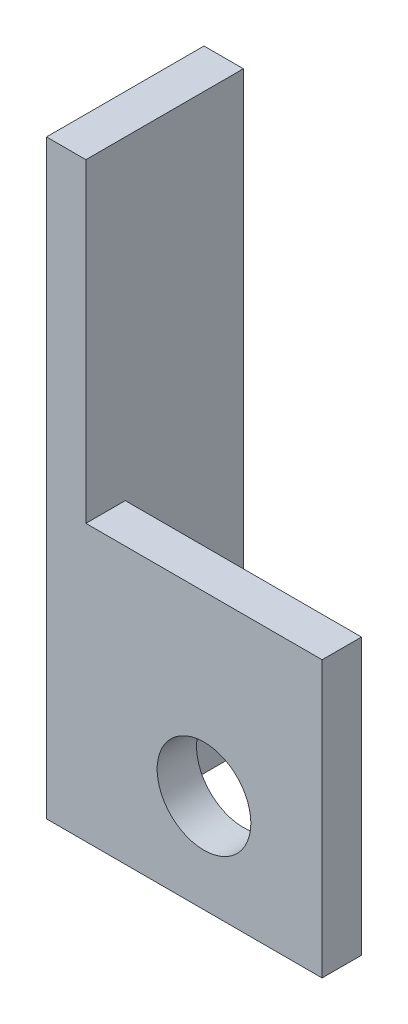
SolidWorks part; units mm, degrees
ref_plane "Front Plane" through (0, 0, 0) normal (0, 0, 1) x (1, 0, 0)
ref_plane "Top Plane" through (0, 0, 0) normal (0, 1, 0) x (1, 0, 0)
ref_plane "Right Plane" through (0, 0, 0) normal (1, 0, 0) x (0, 0, -1)
sketch "Sketch1" plane through (0, 0, 0) normal (0, 0, 1) x (1, 0, 0)
  line L0 (0, 0) -> (7, 0)
  line L1 (7, 0) -> (7, 7)
  line L2 (7, 7) -> (1, 7)
  line L3 (1, 7) -> (1, 15)
  line L4 (1, 15) -> (0, 15)
  line L5 (0, 15) -> (0, 0)
  point P0 (1.2945, 7)
  point P7 (3.7397, 3.6438)
  point P11 (1.4863, 5.8973)
  point P12 (0.3356, 1.4863)
  dimension "D1" = 7
  dimension "D2" = 7
  dimension "D3" = 15
  dimension "D4" = 1
extrude "Boss-Extrude1" add sketch "Sketch1" along normal blind 1
sketch "Sketch2" plane through (0, 0, 0) normal (0, 0, -1) x (-1, 0, 0)
  line L0 (0, 0) -> (0, 15)
  line L1 (0, 15) -> (-1, 15)
  line L2 (-1, 15) -> (-1, 0)
  line L3 (0, 0) -> (-7, 0) construction
  line L4 (-1, 0) -> (0, 0)
extrude "Boss-Extrude2" add sketch "Sketch2" along normal blind 3
sketch "Sketch3" plane through (1, 0, 0) normal (1, 0, 0) x (0, 0, -1)
  line L1 (1, 15) -> (1, -4.1099) construction
  line L2 (-1, 15) -> (3, 15) construction
  circle A0 centre (1, 13) radius 0.7908
  circle A1 centre (1, 9) radius 0.9089
  dimension "D1" = 2
  dimension "D2" = 4
sketch "Sketch4" plane through (0, 0, 1) normal (0, 0, 1) x (1, 0, 0)
  line L0 (7, 7) -> (1, 7) construction
  line L1 (7, 0) -> (7, 7) construction
  circle A0 centre (4, 2.5) radius 1.1901
  dimension "D1" = 4.5
  dimension "D2" = 3
extrude "Cut-Extrude1" cut sketch "Sketch4" against normal blind 3
